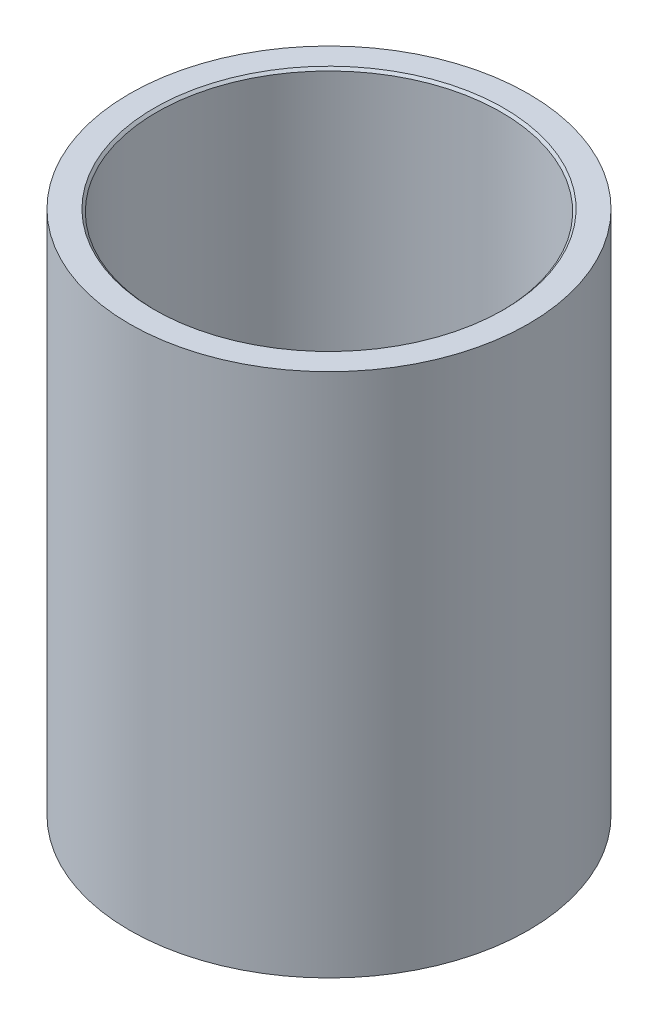
SolidWorks part; units mm, degrees
ref_plane "Front Plane" through (0, 0, 0) normal (0, 0, 1) x (1, 0, 0)
ref_plane "Top Plane" through (0, 0, 0) normal (0, 1, 0) x (1, 0, 0)
ref_plane "Right Plane" through (0, 0, 0) normal (1, 0, 0) x (0, 0, -1)
sketch "Main Revolve Sketch" plane through (0, 0, 0) normal (0, 0, 1) x (1, 0, 0)
  line L0 (0, 0) -> (29.4, 0)
  line L1 (29.4, 0) -> (29.4, 77.4)
  line L2 (29.4, 77.4) -> (25.4, 77.4)
  line L3 (25.4, 77.4) -> (25.4, 4)
  line L4 (25.4, 4) -> (0, 4)
  line L5 (0, 4) -> (0, 0)
  dimension "D1" = 29.4
  dimension "D2" = 4
  dimension "D3" = 4
  dimension "D4" = 77.4
revolve "Cylinder Main Revolve" add sketch "Main Revolve Sketch" angle 360 about L5
fillet "Fillet3" radius 4 1 edges at (-25.4, 4, 0)
chamfer "Chamfer1" distance 0.3569 angle 45 1 edges at (-25.4, 77.4, 0)
